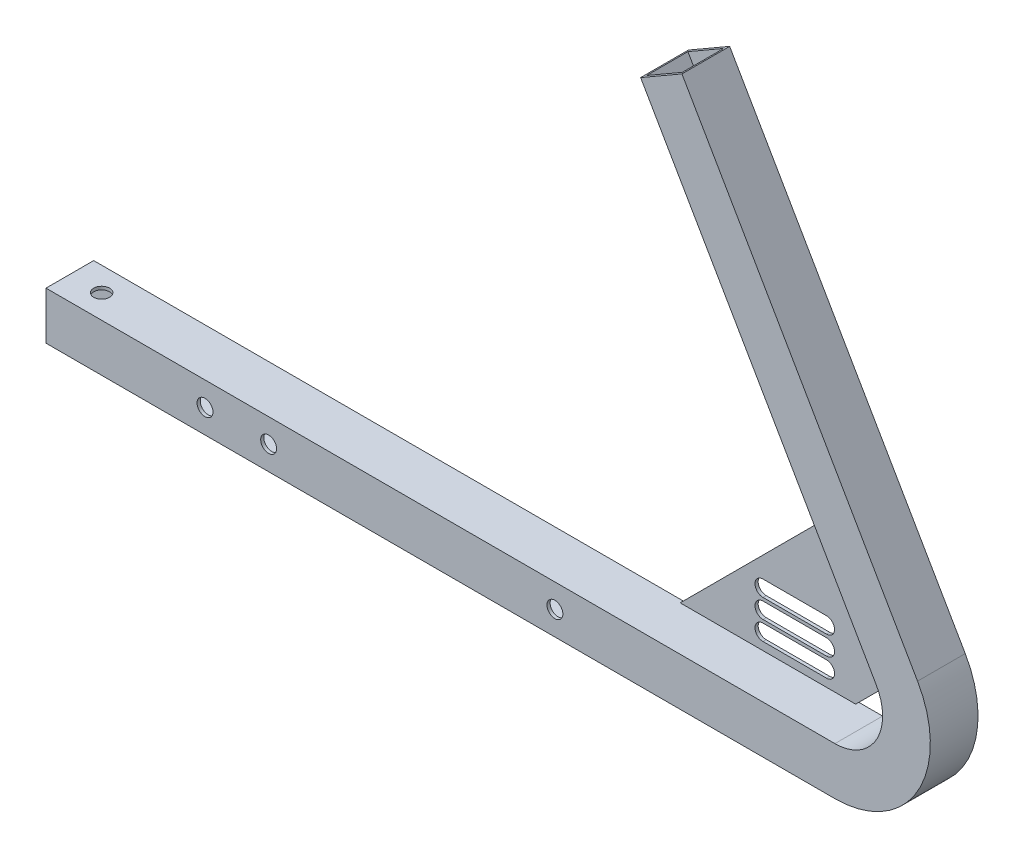
SolidWorks part; units mm, degrees
material "Plain Carbon Steel"
ref_plane "Front Plane" through (0, 0, 0) normal (0, 0, 1) x (1, 0, 0)
ref_plane "Top Plane" through (0, 0, 0) normal (0, 1, 0) x (1, 0, 0)
ref_plane "Right Plane" through (0, 0, 0) normal (1, 0, 0) x (0, 0, -1)
sketch "Sketch1" plane through (0, 0, 0) normal (0, 0, 1) x (1, 0, 0)
  line L0 (102.6529, 330.2) -> (227.3028, 114.3)
  line L1 (161.3117, 0) -> (-468.7061, 0)
  line L2 (69.6573, 311.15) -> (194.3072, 95.25)
  line L3 (161.3117, 38.1) -> (-468.7061, 38.1)
  line L4 (69.6573, 311.15) -> (102.6529, 330.2)
  line L5 (-468.7061, 38.1) -> (-468.7061, 0)
  arc A0 (227.3028, 114.3) -> (161.3117, 0) centre (161.3117, 76.2) cw
  arc A1 (194.3072, 95.25) -> (161.3117, 38.1) centre (161.3117, 76.2) cw
  point P6 (293.2939, 0)
  dimension "D5" = 76.2
  dimension "D1" = 762
  dimension "D2" = 330.2
  dimension "D3" = 60
  dimension "D4" = 254
  dimension "D6" = 38.1
extrude "Boss-Extrude1" add sketch "Sketch1" against normal blind 38.1
shell "Shell1" thickness 2.54
sketch "Sketch3" plane through (-468.7061, 0, 0) normal (-1, 0, 0) x (0, 0, 1)
  line L0 (0, 38.1) -> (0, 0) construction
  line L1 (-35.56, 2.54) -> (-2.54, 2.54)
  line L2 (-35.56, 2.54) -> (-35.56, 35.56)
  line L3 (-35.56, 35.56) -> (-2.54, 35.56)
  line L4 (-2.54, 2.54) -> (-2.54, 35.56)
  line L5 (-35.56, 2.54) -> (-2.54, 35.56) construction
  line L6 (-35.56, 35.56) -> (-2.54, 2.54) construction
  line L7 (-38.1, 38.1) -> (-38.1, 0) construction
  line L8 (-38.1, 0) -> (0, 0) construction
  line L9 (-38.1, 38.1) -> (0, 38.1) construction
  point P0 (-19.05, 19.05)
  dimension "D1" = 2.54
  dimension "D2" = 2.54
  dimension "D3" = 2.54
  dimension "D4" = 2.54
extrude "Cut-Extrude1" cut sketch "Sketch3" against normal up to next
sketch "Sketch5" plane through (0, 0, 0) normal (0, 0, 1) x (1, 0, 0)
  line L1 (-468.7061, 38.1) -> (-468.7061, 0) construction
  line L2 (-468.7061, 0) -> (161.3117, 0) construction
  circle A0 centre (-62.3061, 19.05) radius 6.35
  circle A1 centre (-290.9061, 19.05) radius 6.35
  circle A2 centre (-341.7061, 19.05) radius 6.35
  dimension "D1" = 12.7
  dimension "D2" = 12.7
  dimension "D3" = 12.7
  dimension "D4" = 127
  dimension "D5" = 228.6
  dimension "D6" = 50.8
  dimension "D7" = 19.05
extrude "Cut-Extrude2" cut sketch "Sketch5" against normal through all
ref_plane "Plane1" through (0, 0, -17.78) normal (0, 0, 1) x (1, 0, 0)
sketch "Sketch7" plane through (0, 0, -38.1) normal (0, 0, -1) x (-1, 0, 0)
  line L8 (-144.9018, 180.8228) -> (-194.3072, 95.25)
  line L9 (-196.0533, 91.8406) -> (-142.3127, 38.1)
  line L10 (-142.3127, 38.1) -> (-2.179, 38.1)
  line L11 (-2.179, 38.1) -> (-144.9018, 180.8228)
  arc A2 (-194.3072, 95.25) -> (-196.0533, 91.8406) centre (-161.3117, 76.2) ccw
  dimension "D1" = 38.1
  dimension "D2" = 31.2495
  dimension "D3" = 32.9956
  dimension "D4" = 65.9911
  dimension "D5" = 82.401
  dimension "D6" = 84.9901
  dimension "D7" = 225.1238
  dimension "D8" = 38.1
extrude "Boss-Extrude4" add sketch "Sketch7" against normal blind 2.54
sketch "Sketch8" plane through (-117.3176, 203.2, 0) normal (-0.5, 0.866, 0) x (0.866, 0.5, 0)
  line L4 (215.9, 0) -> (254, 0)
  line L5 (254, 0) -> (254, 38.1)
  line L6 (254, 38.1) -> (215.9, 38.1)
  line L7 (215.9, 38.1) -> (215.9, 0)
  line L8 (215.9, 0) -> (254, 0)
  line L9 (254, 0) -> (254, 38.1)
  line L10 (254, 38.1) -> (215.9, 38.1)
  line L11 (215.9, 38.1) -> (215.9, 0)
  line L12 (251.46, 2.54) -> (251.46, 35.56)
  line L13 (218.44, 2.54) -> (251.46, 2.54)
  line L14 (218.44, 35.56) -> (218.44, 2.54)
  line L15 (251.46, 35.56) -> (218.44, 35.56)
  line L16 (251.46, 2.54) -> (251.46, 35.56)
  line L17 (218.44, 2.54) -> (251.46, 2.54)
  line L18 (218.44, 35.56) -> (218.44, 2.54)
  line L19 (251.46, 35.56) -> (218.44, 35.56)
  dimension "D1" = 0
  dimension "D2" = 0
extrude "Boss-Extrude5" add sketch "Sketch8" along normal blind 127
sketch "Sketch9" plane through (0, 38.1, 0) normal (0, 1, 0) x (1, 0, 0)
  line L0 (-468.7061, 38.1) -> (-468.7061, 0) construction
  line L1 (161.3117, 0) -> (-468.7061, 0) construction
  circle A0 centre (-443.3061, 19.05) radius 6.35
  dimension "D1" = 12.7
  dimension "D2" = 25.4
  dimension "D3" = 19.05
extrude "Cut-Extrude3" cut sketch "Sketch9" against normal up to next
sketch "Sketch11" plane through (0, 0, -38.1) normal (0, 0, -1) x (-1, 0, 0)
  line L0 (-119.0917, 44.45) -> (-68.2917, 44.45) construction
  line L1 (-68.2917, 57.15) -> (-119.0917, 57.15) construction
  line L2 (-68.2917, 87.63) -> (-119.0917, 87.63) construction
  line L3 (-119.0917, 74.93) -> (-68.2917, 74.93) construction
  line L4 (-68.2917, 72.39) -> (-119.0917, 72.39) construction
  line L5 (-119.0917, 59.69) -> (-68.2917, 59.69) construction
  line L6 (-119.0917, 44.45) -> (-68.2917, 44.45)
  line L7 (-68.2917, 57.15) -> (-119.0917, 57.15)
  line L8 (-68.2917, 87.63) -> (-119.0917, 87.63)
  line L9 (-119.0917, 74.93) -> (-68.2917, 74.93)
  line L10 (-68.2917, 72.39) -> (-119.0917, 72.39)
  line L11 (-119.0917, 59.69) -> (-68.2917, 59.69)
  arc A0 (-68.2917, 74.93) -> (-68.2917, 87.63) centre (-68.2917, 81.28) ccw construction
  arc A1 (-68.2917, 59.69) -> (-68.2917, 72.39) centre (-68.2917, 66.04) ccw construction
  arc A2 (-68.2917, 44.45) -> (-68.2917, 57.15) centre (-68.2917, 50.8) ccw construction
  arc A3 (-119.0917, 57.15) -> (-119.0917, 44.45) centre (-119.0917, 50.8) ccw construction
  arc A4 (-119.0917, 87.63) -> (-119.0917, 74.93) centre (-119.0917, 81.28) ccw construction
  arc A5 (-119.0917, 72.39) -> (-119.0917, 59.69) centre (-119.0917, 66.04) ccw construction
  arc A6 (-68.2917, 74.93) -> (-68.2917, 87.63) centre (-68.2917, 81.28) ccw
  arc A7 (-68.2917, 59.69) -> (-68.2917, 72.39) centre (-68.2917, 66.04) ccw
  arc A8 (-68.2917, 44.45) -> (-68.2917, 57.15) centre (-68.2917, 50.8) ccw
  arc A9 (-119.0917, 57.15) -> (-119.0917, 44.45) centre (-119.0917, 50.8) ccw
  arc A10 (-119.0917, 87.63) -> (-119.0917, 74.93) centre (-119.0917, 81.28) ccw
  arc A11 (-119.0917, 72.39) -> (-119.0917, 59.69) centre (-119.0917, 66.04) ccw
extrude "Cut-Extrude5" cut sketch "Sketch11" against normal through all both and the other way through all
sketch "Sketch12" plane through (0, 0, -38.1) normal (0, 0, -1) x (-1, 0, 0)
  circle A1 centre (-35.3665, 408.6434) radius 6.35
  circle A2 centre (-35.3665, 408.6434) radius 6.35
  dimension "D1" = 0
extrude "Cut-Extrude6" cut sketch "Sketch12" against normal up to next
sketch "Sketch16" plane through (0, 0, -38.1) normal (0, 0, -1) x (-1, 0, 0)
  line L0 (-68.2917, 87.63) -> (-119.0917, 87.63) construction
  circle A0 centre (-21.5325, 19.05) radius 6.35 construction
  dimension "D1" = 12.7
  dimension "D2" = 97.5592
  dimension "D3" = 68.58
